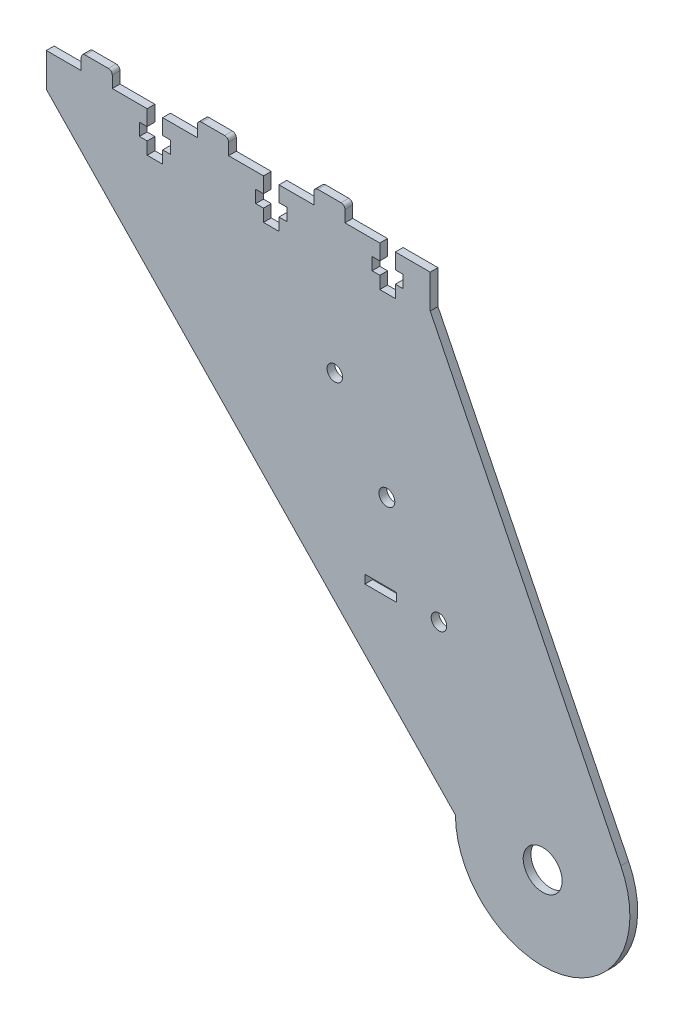
SolidWorks part; units mm, degrees
ref_plane "前视基准面" through (0, 0, 0) normal (0, 0, 1) x (1, 0, 0)
ref_plane "上视基准面" through (0, 0, 0) normal (0, 1, 0) x (1, 0, 0)
ref_plane "右视基准面" through (0, 0, 0) normal (1, 0, 0) x (0, 0, -1)
sketch "草图1" plane through (0, 0, 0) normal (0, 0, 1) x (1, 0, 0)
  line L0 (-19.7627, 31.422) -> (7.0984, -10.75) construction
  line L2 (-36.15, 68.25) -> (-36.15, 58.15) construction
  line L15 (-38.15, 66.25) -> (-38.15, 62.25)
  line L16 (-38.15, 62.25) -> (-40.15, 62.25)
  line L17 (-40.15, 62.25) -> (-40.15, 59.05)
  line L18 (-40.15, 59.05) -> (-38.15, 59.05)
  line L19 (-38.15, 59.05) -> (-38.15, 55.85)
  line L20 (-38.15, 55.85) -> (-34.15, 55.85)
  line L21 (-38.15, 66.25) -> (-47.15, 66.25)
  line L22 (-51.15, 66.25) -> (-51.15, 70.25) construction
  line L23 (-47.15, 66.25) -> (-55.15, 66.25) construction
  line L24 (-47.15, 66.25) -> (-47.15, 70.25)
  line L25 (-47.15, 70.25) -> (-55.15, 70.25)
  line L26 (-55.15, 66.25) -> (-55.15, 70.25)
  line L27 (-25.15, 66.25) -> (-17.15, 66.25) construction
  line L28 (-21.15, 66.25) -> (-21.15, 70.25) construction
  line L29 (-17.15, 66.25) -> (-17.15, 70.25)
  line L30 (-25.15, 70.25) -> (-17.15, 70.25)
  line L31 (-25.15, 66.25) -> (-25.15, 70.25)
  line L32 (-34.15, 66.25) -> (-25.15, 66.25)
  line L33 (-34.15, 59.05) -> (-34.15, 55.85)
  line L34 (-32.15, 59.05) -> (-34.15, 59.05)
  line L35 (-32.15, 62.25) -> (-32.15, 59.05)
  line L36 (-34.15, 62.25) -> (-32.15, 62.25)
  line L37 (-34.15, 66.25) -> (-34.15, 62.25)
  line L38 (-94.15, 66.25) -> (-94.15, 57.55)
  line L39 (-94.15, 57.55) -> (11.35, -51.75)
  line L40 (-68.15, 66.25) -> (-68.15, 62.25)
  line L41 (-68.15, 62.25) -> (-70.15, 62.25)
  line L42 (-70.15, 62.25) -> (-70.15, 59.05)
  line L43 (-70.15, 59.05) -> (-68.15, 59.05)
  line L44 (-68.15, 59.05) -> (-68.15, 55.85)
  line L45 (-68.15, 66.25) -> (-77.15, 66.25)
  line L46 (-6.15, 68.25) -> (-6.15, 58.15) construction
  line L49 (-64.15, 55.85) -> (-68.15, 55.85)
  line L50 (-64.15, 59.05) -> (-64.15, 55.85)
  line L51 (-62.15, 59.05) -> (-64.15, 59.05)
  line L52 (-62.15, 62.25) -> (-62.15, 59.05)
  line L53 (-64.15, 62.25) -> (-62.15, 62.25)
  line L54 (-64.15, 66.25) -> (-64.15, 62.25)
  line L55 (-55.15, 66.25) -> (-64.15, 66.25)
  line L58 (-8.15, 66.25) -> (-17.15, 66.25)
  line L59 (-94.15, 66.25) -> (-85.15, 66.25)
  line L60 (-85.15, 66.25) -> (-85.15, 70.25)
  line L61 (-77.15, 70.25) -> (-85.15, 70.25)
  line L62 (-77.15, 66.25) -> (-77.15, 70.25)
  line L63 (4.85, 66.25) -> (4.85, 57.55)
  line L65 (7.0984, -10.75) -> (-7.9016, -10.75) construction
  line L66 (-8.15, 66.25) -> (-8.15, 62.25)
  line L67 (-8.15, 62.25) -> (-10.15, 62.25)
  line L68 (-10.15, 62.25) -> (-10.15, 59.05)
  line L69 (-10.15, 59.05) -> (-8.15, 59.05)
  line L70 (-8.15, 59.05) -> (-8.15, 55.85)
  line L74 (-4.15, 66.25) -> (4.85, 66.25)
  line L75 (-4.15, 55.85) -> (-8.15, 55.85)
  line L76 (-4.15, 59.05) -> (-4.15, 55.85)
  line L77 (-2.15, 59.05) -> (-4.15, 59.05)
  line L78 (-2.15, 62.25) -> (-2.15, 59.05)
  line L79 (-4.15, 62.25) -> (-2.15, 62.25)
  line L80 (-4.15, 66.25) -> (-4.15, 62.25)
  line L86 (4.85, 57.55) -> (54.0146, -41.7681)
  line L87 (-12.0016, -11.85) -> (-3.8016, -11.85)
  line L88 (-12.0016, -11.85) -> (-12.0016, -9.65)
  line L89 (-12.0016, -9.65) -> (-3.8016, -9.65)
  line L90 (-3.8016, -11.85) -> (-3.8016, -9.65)
  line L91 (-12.0016, -11.85) -> (-3.8016, -9.65) construction
  line L92 (-12.0016, -9.65) -> (-3.8016, -11.85) construction
  circle A0 centre (-36.15, 68.25) radius 2 construction
  circle A1 centre (-19.7627, 31.422) radius 2
  circle A2 centre (7.0984, -10.75) radius 2
  circle A3 centre (33.85, -51.75) radius 22.5 construction
  arc A6 (11.35, -51.75) -> (54.0146, -41.7681) centre (33.85, -51.75) ccw
  circle A7 centre (33.85, -52.75) radius 5.02
  circle A8 centre (-6.3322, 10.336) radius 2.05
  point P39 (-36.15, 55.85)
  point P61 (-66.15, 55.85)
  point P91 (-6.15, 55.85)
  dimension "D17" = 10.04
  dimension "D20" = 4
  dimension "D12" = 4
  dimension "D5" = 4
  dimension "D6" = 2
  dimension "D7" = 3.2
  dimension "D8" = 3.2
  dimension "D9" = 15
  dimension "D10" = 8
  dimension "D11" = 4
  dimension "D13" = 8.2
  dimension "D14" = 2.2
  dimension "D15" = 10.1
  dimension "D16" = 15
extrude "凸台-拉伸1" add sketch "草图1" along normal blind 2
sketch "草图2" plane through (0, 66.25, 0) normal (0, 1, 0) x (1, 0, 0)
  line L0 (-8.15, -1) -> (-4.15, -1)
  line L1 (-8.15, -2) -> (-8.15, 0) construction
  line L2 (-4.15, -2) -> (-4.15, 0) construction
  circle A0 centre (-6.15, -1) radius 2
fillet "圆角1" radius 1 6 edges at (-17.15, 70.25, 1) (-25.15, 70.25, 1) (-47.15, 70.25, 1) (-55.15, 70.25, 1) (-77.15, 70.25, 1) (-85.15, 70.25, 1)
